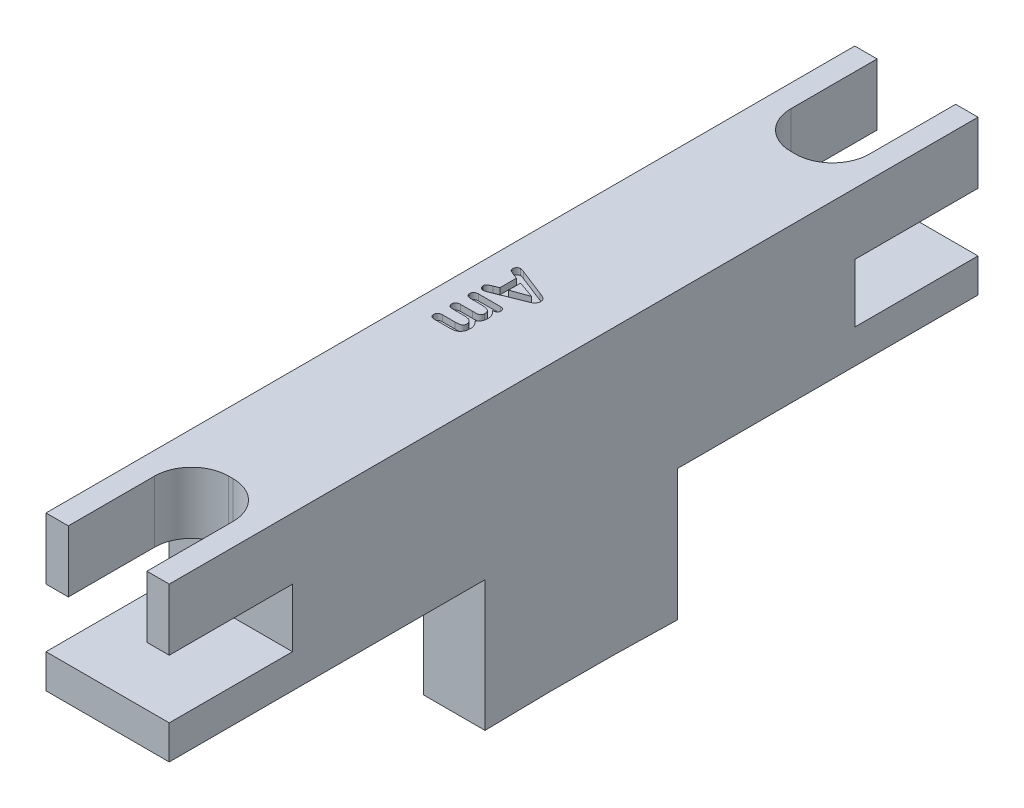
SolidWorks part; units mm, degrees
ref_plane "Front Plane" through (0, 0, 0) normal (0, 0, 1) x (1, 0, 0)
ref_plane "Top Plane" through (0, 0, 0) normal (0, 1, 0) x (1, 0, 0)
ref_plane "Right Plane" through (0, 0, 0) normal (1, 0, 0) x (0, 0, -1)
sketch "Sketch2" plane through (0, 0, 0) normal (0, 1, 0) x (1, 0, 0)
  line L1 (0, 0) -> (10.16, 0)
  line L2 (0, 0) -> (0, 66.675)
  line L3 (0, 66.675) -> (10.16, 66.675)
  line L4 (10.16, 0) -> (10.16, 66.675)
  dimension "D1" = 66.675
  dimension "D2" = 10.16
extrude "Boss-Extrude1" add sketch "Sketch2" along normal blind 12.7
sketch "Sketch3" plane through (0, 0, 0) normal (0, -1, 0) x (1, 0, 0)
  line L0 (10.16, -66.675) -> (0, -66.675) construction
  line L1 (5.08, 0) -> (10.16, 0)
  line L2 (5.08, 0) -> (5.08, -66.675)
  line L3 (5.08, -66.675) -> (10.16, -66.675)
  line L4 (10.16, 0) -> (10.16, -66.675)
  line L5 (0, -66.675) -> (0, 0) construction
  line L6 (0, 0) -> (10.16, 0) construction
  line L7 (-16.0623, -37.465) -> (21.3262, -37.465) construction
  line L8 (-9.1988, -29.21) -> (67.1361, -29.21) construction
  line L9 (5.08, -37.465) -> (5.08, -29.21) construction
  line L10 (-21.0326, -20.955) -> (28.4478, -20.955) construction
  line L11 (7.62, 0) -> (7.62, -66.675) construction
  line L12 (-27.1779, -45.72) -> (27.7068, -45.72) construction
  line L13 (5.08, -41.91) -> (10.16, -41.91)
  line L14 (10.16, -48.895) -> (5.08, -48.895)
  line L15 (10.16, -48.895) -> (10.16, -42.545) construction
  line L16 (10.16, -42.545) -> (5.08, -42.545)
  line L17 (5.08, -48.895) -> (5.08, -42.545) construction
  line L18 (10.16, -48.895) -> (5.08, -42.545) construction
  line L19 (10.16, -42.545) -> (5.08, -48.895) construction
  line L20 (10.16, -40.64) -> (5.08, -40.64)
  line L21 (10.16, -40.64) -> (10.16, -34.29)
  line L22 (10.16, -34.29) -> (5.08, -34.29)
  line L23 (5.08, -40.64) -> (5.08, -34.29)
  line L24 (10.16, -40.64) -> (5.08, -34.29) construction
  line L25 (10.16, -34.29) -> (5.08, -40.64) construction
  line L26 (10.16, -32.385) -> (5.08, -32.385)
  line L27 (10.16, -32.385) -> (10.16, -26.035)
  line L28 (10.16, -26.035) -> (5.08, -26.035)
  line L29 (5.08, -32.385) -> (5.08, -26.035)
  line L30 (10.16, -32.385) -> (5.08, -26.035) construction
  line L31 (10.16, -26.035) -> (5.08, -32.385) construction
  line L32 (10.16, -24.13) -> (5.08, -24.13)
  line L33 (10.16, -24.13) -> (10.16, -17.78)
  line L34 (10.16, -17.78) -> (5.08, -17.78)
  line L35 (5.08, -24.13) -> (5.08, -17.78)
  line L36 (10.16, -24.13) -> (5.08, -17.78) construction
  line L37 (10.16, -17.78) -> (5.08, -24.13) construction
  point P16 (5.08, -33.3375)
  point P17 (5.08, -33.3375)
  point P24 (7.62, -45.72)
  point P29 (7.62, -29.21)
  point P30 (7.62, -37.465)
  point P41 (7.62, -20.955)
  line M4 (10.16, -66.675) -> (10.16, 0)
  dimension "D1" = 5.08
  dimension "D2" = 5.08
  dimension "D3" = 8.255
  dimension "D4" = 8.255
  dimension "D5" = 8.255
  dimension "D6" = 5.08
  dimension "D7" = 6.35
  dimension "D8" = 6.35
  dimension "D9" = 6.35
  dimension "D10" = 6.35
  dimension "D11" = 1.27
extrude "Boss-Extrude2" add sketch "Sketch3" along normal blind 12.7 contours L4 L22 L2 L20 | L26 L2 L22 M4 | L4 L28 L2 L26 | L4 L20 L2 L13
sketch "Sketch4" plane through (0, 0, 0) normal (0, 0, 1) x (1, 0, 0)
  line L0 (0, 12.7) -> (10.16, 12.7) construction
  line L1 (0, 7.62) -> (1.8415, 7.62)
  line L2 (0, 7.62) -> (0, 2.794)
  line L3 (0, 2.794) -> (10.16, 2.794)
  line L4 (10.16, 7.62) -> (10.16, 2.794)
  line L5 (1.8415, 12.7) -> (8.3185, 12.7)
  line L6 (1.8415, 12.7) -> (1.8415, 7.62)
  line L8 (8.3185, 12.7) -> (8.3185, 7.62)
  line L9 (8.3185, 7.62) -> (10.16, 7.62)
  line L10 (10.16, 12.7) -> (10.16, 0) construction
  line L11 (0, 12.7) -> (0, 0) construction
  point P10 (5.08, 12.7)
  dimension "D2" = 6.477
  dimension "D3" = 4.826
  dimension "D4" = 5.08
extrude "Cut-Extrude1" cut sketch "Sketch4" against normal blind 10.16
ref_plane "Plane1" through (0, 0, -33.3375) normal (0, 0, 1) x (1, 0, 0)
fillet "Fillet2" radius 3.048 2 edges at (8.3185, 10.16, -10.16) (1.8415, 10.16, -10.16)
mirror "Mirror1" about plane through (0, 0, -33.3375) normal (0, 0, 1) of "Fillet2", "Cut-Extrude1"
sketch "Sketch5" plane through (5.08, 0, 0) normal (-1, 0, 0) x (0, 0, 1)
  line L0 (-33.3375, -10.668) -> (-33.3375, -12.7) construction
  line L2 (-66.675, -12.7) -> (0, -12.7)
  line L3 (-66.675, -12.7) -> (-66.675, 0) construction
  line L4 (-26.035, -12.7) -> (-41.91, -12.7) construction
  line L5 (0, -12.7) -> (0, 0) construction
  arc A0 (-66.675, -12.7) -> (0, -12.7) centre (-33.3375, -285.1557) cw
  dimension "D1" = 2.032
  dimension "D2" = 12.7
extrude "Cut-Extrude4" cut sketch "Sketch5" against normal through all
fillet "Fillet1" [suppressed] radius 2.54
sketch "Sketch6" plane through (0, 12.7, 0) normal (0, 1, 0) x (1, 0, 0)
  line L0 (1.8415, 7.112) -> (1.8415, 59.563) construction
  arc A0 (4.8895, 10.16) -> (1.8415, 7.112) centre (4.8895, 7.112) ccw construction
  text T0 "Am\r\n\r\n" font "Arial Rounded MT Bold" height 3.5
extrude "Cut-Extrude5" cut sketch "Sketch6" against normal blind 0.508
